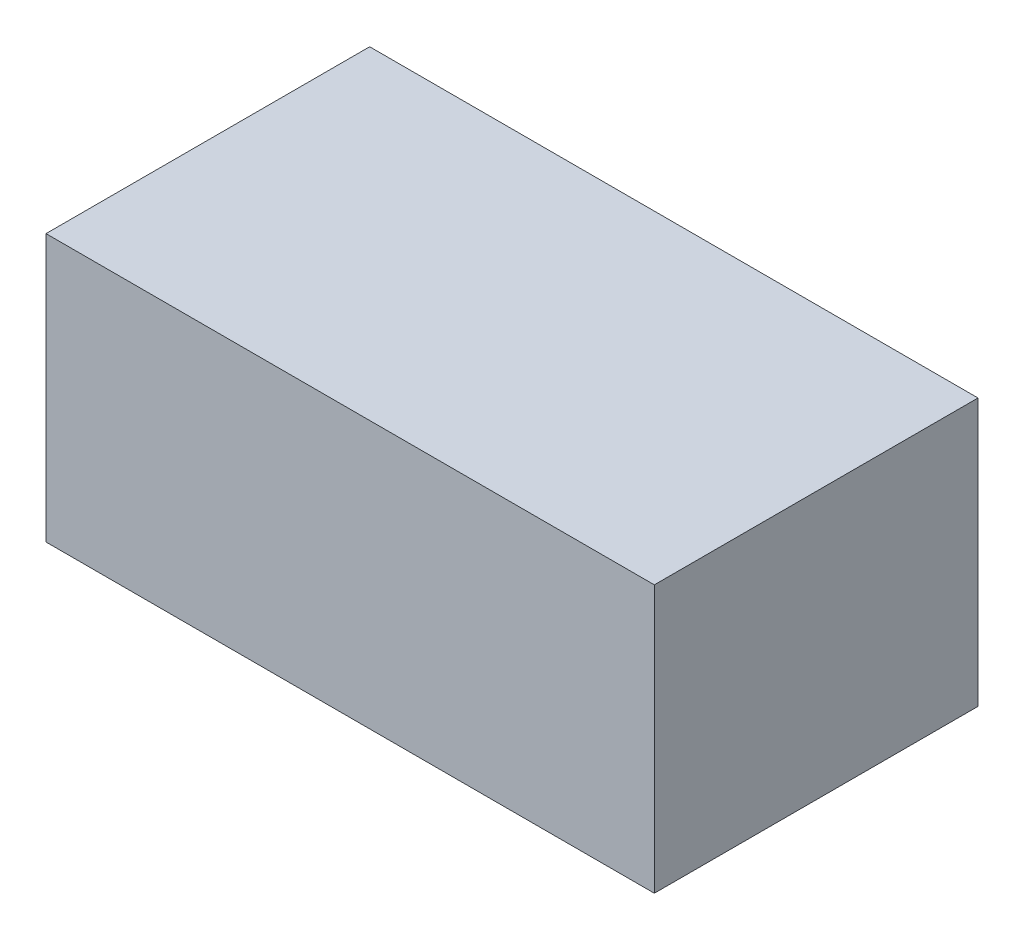
SolidWorks part; units mm, degrees
ref_plane "Front Plane" through (0, 0, 0) normal (0, 0, 1) x (1, 0, 0)
ref_plane "Top Plane" through (0, 0, 0) normal (0, 1, 0) x (1, 0, 0)
ref_plane "Right Plane" through (0, 0, 0) normal (1, 0, 0) x (0, 0, -1)
sketch "Sketch1" plane through (0, 0, 0) normal (0, 1, 0) x (1, 0, 0)
  line L5 (0, 0) -> (56.939, 0)
  line L6 (0, 0) -> (0, 30.2933)
  line L7 (0, 30.2933) -> (56.939, 30.2933)
  line L8 (56.939, 0) -> (56.939, 30.2933)
extrude "Boss-Extrude1" add sketch "Sketch1" along normal blind 25 contours L6 L7 L8 L5
scale "Scale1" scale about centroid uniform scaling yes scale factor 0.5
